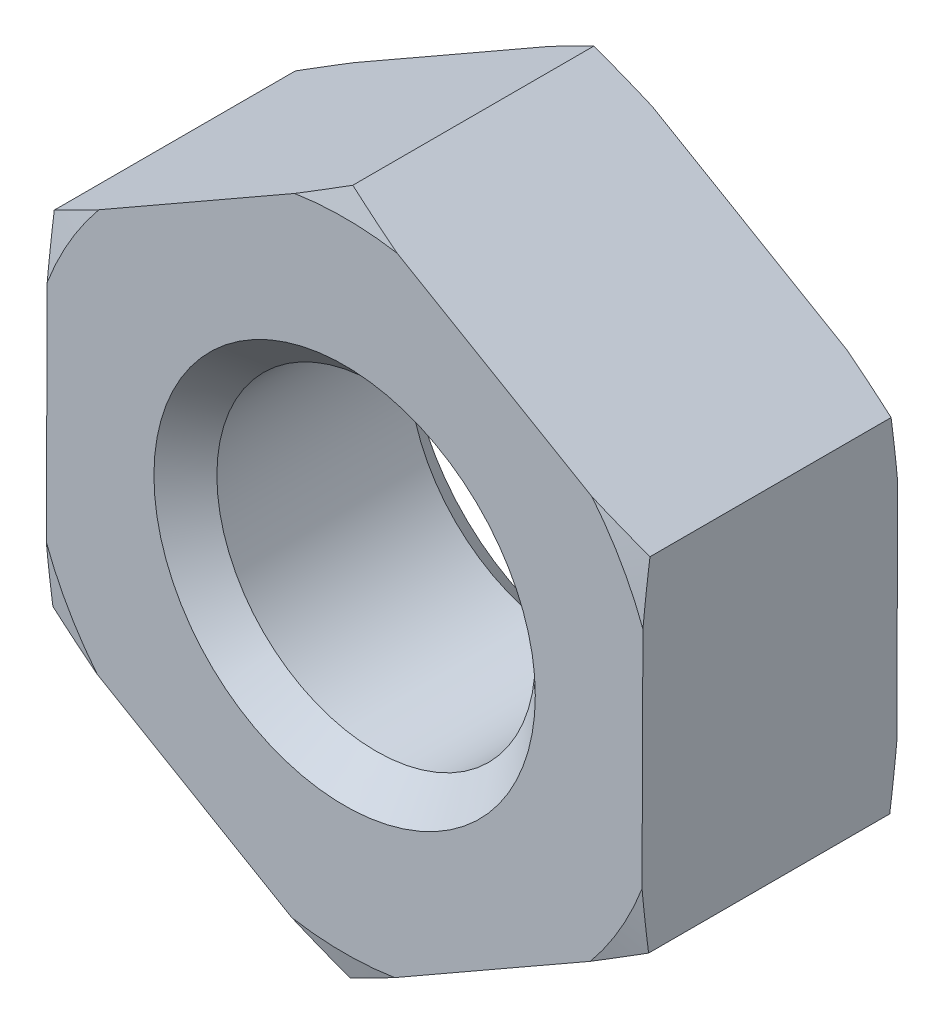
SolidWorks part; units mm, degrees
extrude "基体-拉伸" add sketch "草图1" along normal blind 1.6
sketch "草图1" plane through (0, 0, 0) normal (0, 0, 1) x (1, 0, 0)
  line L0 (-26.8088, 0) -> (37.1748, 0) construction
  line L1 (0, 25.0215) -> (0, -25.0215) construction
  line L3 (0.0085, 2.16) -> (-1.8664, 1.0873)
  line L4 (-1.8664, 1.0873) -> (-1.8748, -1.0726)
  line L5 (-1.8748, -1.0726) -> (-0.0085, -2.16)
  line L6 (-0.0085, -2.16) -> (1.8664, -1.0873)
  line L7 (1.8664, -1.0873) -> (1.8748, 1.0726)
  line L8 (1.8748, 1.0726) -> (0.0085, 2.16)
  circle A0 centre (0, 0) radius 1.8706 construction
  circle A1 centre (0, 0) radius 1
  dimension "D" = 2
  dimension "e" = 4.32
cosmetic thread "装饰螺纹线1"
chamfer "倒角1" distance 0.1976 angle 45 2 edges at (1, 0, 0) (1, 0, 1.6)
material "A2-70级"
ref_plane "基准面1" through (0, 0, 0) normal (0, 0, 1) x (1, 0, 0)
ref_plane "基准面2" through (0, 0, 0) normal (0, 1, 0) x (1, 0, 0)
ref_plane "基准面3" through (0, 0, 0) normal (1, 0, 0) x (0, 0, -1)
sketch "尺寸草图" plane through (0, 0, 0) normal (0, 0, 1) x (1, 0, 0)
  line L0 (0, 0) -> (35.1249, 0)
  line L1 (35.1249, 0) -> (37.4249, 0)
  line L2 (37.4249, 0) -> (40.5249, 0)
  line L3 (-1.9048, 0) -> (0, 0)
  point P3 (2, 0)
  point P4 (1.5, 0)
  point P5 (4.32, 0)
  point P6 (1.6, 0)
  point P7 (6.4, 0)
  point P8 (4, 0)
  dimension "D" = 2
  dimension "e" = 4.32
  dimension "P" = 1.5
  dimension "m" = 1.6
  dimension "mw" = 6.4
  dimension "s" = 4
  dimension "da" = 2.3
  dimension "dw" = 3.1
  dimension "D1" = 1.9048
sketch "草图2" plane through (0, 0, 0) normal (0, 0, -1) x (-1, 0, 0)
  circle A0 centre (0, 0) radius 2
  circle A1 centre (0, 0) radius 1 construction
  dimension "s" = 4
extrude "切除-拉伸1" cut sketch "草图2" against normal through all draft 75 flip side to cut
sketch "草图3" plane through (0, 0, 1.6) normal (0, 0, 1) x (1, 0, 0)
  circle A0 centre (0, 0) radius 2
  dimension "D1" = 4
extrude "切除-拉伸2" cut sketch "草图3" against normal through all draft 75 flip side to cut
equation "\"e@草图1\" = \"e@尺寸草图\""
equation "\"D1@尺寸草图\" = \"D@尺寸草图\" / 1.05"
equation "\"D@草图1\" = \"D@尺寸草图\""
equation "\"m@基体-拉伸\" = \"m@尺寸草图\""
equation "\"D1@草图3\" = \"s@尺寸草图\""
equation "\"s@草图2\" = \"s@尺寸草图\""
equation "\"D2@装饰螺纹线1\" =\"D@尺寸草图\""
equation "\"D1@倒角1\" =  ( \"da@尺寸草图\" - \"D1@尺寸草图\" )  / 2"
